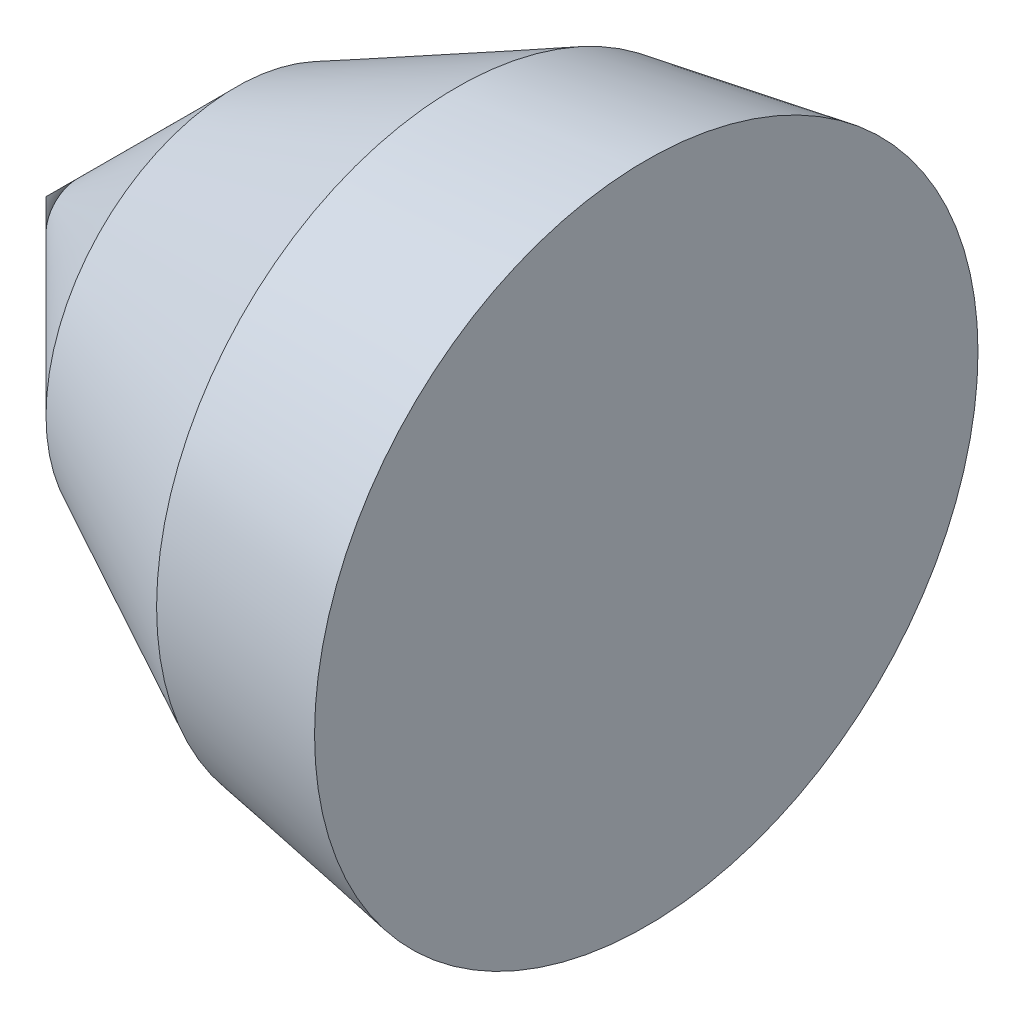
SolidWorks part; units mm, degrees
ref_plane "Front Plane" through (0, 0, 0) normal (0, 0, 1) x (1, 0, 0)
ref_plane "Top Plane" through (0, 0, 0) normal (0, 1, 0) x (1, 0, 0)
ref_plane "Right Plane" through (0, 0, 0) normal (1, 0, 0) x (0, 0, -1)
sketch "Sketch1" plane through (0, 0, 0) normal (0, 0, 1) x (1, 0, 0)
  line L0 (0, 0) -> (0, 21)
  line L1 (0, 21) -> (-12, 19)
  line L2 (-12, 19) -> (-26, 12)
  line L3 (-26, 12) -> (-38, 0)
  line L4 (-38, 0) -> (0, 0)
  line L5 (-10, 0) -> (1000, 0) construction
revolve "Revolve1" add sketch "Sketch1" angle 360 about L5
